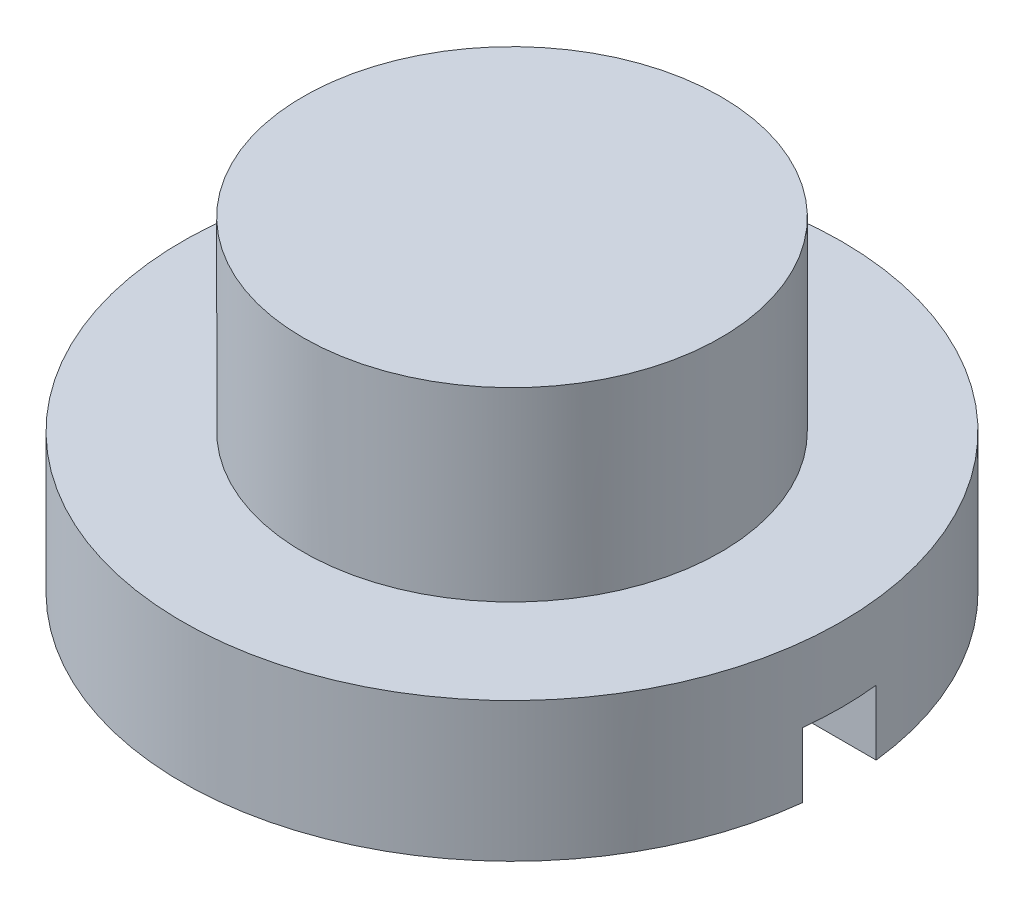
SolidWorks part; units mm, degrees
ref_plane "Front Plane" through (0, 0, 0) normal (0, 0, 1) x (1, 0, 0)
ref_plane "Top Plane" through (0, 0, 0) normal (0, 1, 0) x (1, 0, 0)
ref_plane "Right Plane" through (0, 0, 0) normal (1, 0, 0) x (0, 0, -1)
sketch "Sketch1" plane through (0, 0, 0) normal (0, 1, 0) x (1, 0, 0)
  circle A0 centre (-11.7006, 6.2787) radius 5.715
  dimension "D1" = 11.43
extrude "Boss-Extrude1" add sketch "Sketch1" along normal blind 5.08
sketch "Sketch2" plane through (0, 0, 0) normal (0, -1, 0) x (1, 0, 0)
  circle A0 centre (-11.7006, -6.2787) radius 9.017
  point P3 (-9.888, -5.3199)
  dimension "D1" = 18.034
extrude "Boss-Extrude2" add sketch "Sketch2" along normal blind 3.81
sketch "Sketch3" plane through (0, -3.81, 0) normal (0, -1, 0) x (1, 0, 0)
  line L1 (-21.0447, -7.2841) -> (-2.3565, -7.2841)
  line L2 (-21.0447, -7.2841) -> (-21.0447, -5.2733)
  line L3 (-21.0447, -5.2733) -> (-2.3565, -5.2733)
  line L4 (-2.3565, -7.2841) -> (-2.3565, -5.2733)
  line L5 (-21.0447, -7.2841) -> (-2.3565, -5.2733) construction
  line L6 (-21.0447, -5.2733) -> (-2.3565, -7.2841) construction
  point P0 (-11.7006, -6.2787)
extrude "Cut-Extrude1" cut sketch "Sketch3" against normal blind 1.778
